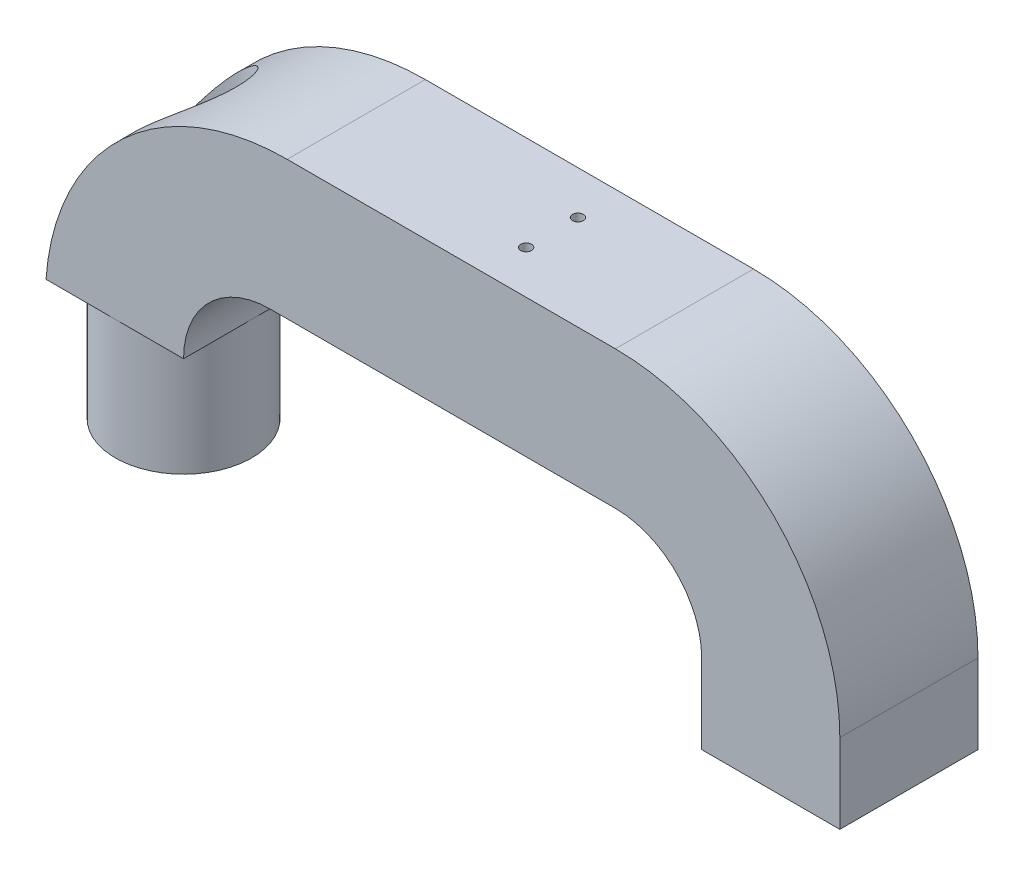
SolidWorks part; units mm, degrees
ref_plane "Front Plane" through (0, 0, 0) normal (0, 0, 1) x (1, 0, 0)
ref_plane "Top Plane" through (0, 0, 0) normal (0, 1, 0) x (1, 0, 0)
ref_plane "Right Plane" through (0, 0, 0) normal (1, 0, 0) x (0, 0, -1)
sketch "Sketch1" plane through (0, 0, 0) normal (0, 0, 1) x (1, 0, 0)
  line L0 (0, 0) -> (80, 0)
  line L1 (0, 0) -> (0, 60)
  line L2 (140, 200) -> (330, 200)
  line L3 (460, 70) -> (460, 24)
  line L4 (80, 0) -> (80, 70)
  line L5 (0.3576, 70) -> (0, 70)
  line L6 (460, 24) -> (380, 24)
  line L7 (130, 120) -> (235, 120)
  line L9 (235, 120) -> (330, 120)
  line L10 (380, 70) -> (380, 24)
  arc A0 (140, 200) -> (0, 60) centre (140, 60) ccw
  arc A1 (330, 200) -> (460, 70) centre (330, 70) cw
  arc A2 (330, 120) -> (380, 70) centre (330, 70) cw
  arc A3 (130, 120) -> (80, 70) centre (130, 70) ccw
  point P11 (0, 200)
  point P14 (460, 200)
  dimension "D6" = 140
  dimension "D7" = 130
  dimension "D9" = 50
  dimension "D1" = 50
  dimension "D2" = 200
  dimension "D3" = 176
  dimension "D4" = 80
  dimension "D5" = 80
  dimension "D8" = 80
extrude "Boss-Extrude1" add sketch "Sketch1" along normal blind 80 contours L2 A1 L3 L6 L10 A2 L9 L7 A3 L4 L0 L1 A0
sketch "Sketch5" plane through (0, 0, 0) normal (0, -1, 0) x (1, 0, 0)
  circle A0 centre (40, 40) radius 39.5
  circle A1 centre (40, 40) radius 30.5
  dimension "D1" = 61
  dimension "D2" = 79
extrude "Cut-Extrude-Thin2" cut sketch "Sketch5" against normal blind 70 thin contours A0
sketch "Sketch6" plane through (0, 0, 0) normal (0, -1, 0) x (1, 0, 0)
  circle A0 centre (40, 40) radius 30.5
  dimension "D1" = 61
extrude "Cut-Extrude9" cut sketch "Sketch6" against normal through all
sketch "Sketch7" plane through (0, 200, 0) normal (0, 1, 0) x (1, 0, 0)
  line L0 (330, -25) -> (253.35, -25)
  line L1 (330, -80) -> (330, 0) construction
  line L2 (253.35, -25) -> (253.35, -55)
  line L3 (140, 0) -> (330, 0) construction
  dimension "D1" = 76.65
  dimension "D2" = 30
  dimension "D3" = 25
hole_wizard "Ø3.0mm Dowel Hole1" positions "3DSketch1" profile "Sketch8" hole size "Ø3.0" standard "ISO" end condition through all
sketch3d "3DSketch1"
  point P0 (253.35, 200, 55)
  point P3 (253.35, 200, 25)
sketch "Sketch8" plane through (253.35, 200, 55) normal (1, 0, 0) x (0, 0, 1)
  line L0 (0, 0) -> (0, 200)
  line L1 (0, 200) -> (3.15, 200)
  line L2 (3.15, 200) -> (3.15, 0)
  line L5 (3.15, 0) -> (0, 0)
  line L11 (0, -6.35) -> (0, 107.95) construction
  dimension "Thru Hole Dia." = 6.3
  dimension "Thru Hole Depth" = 200
